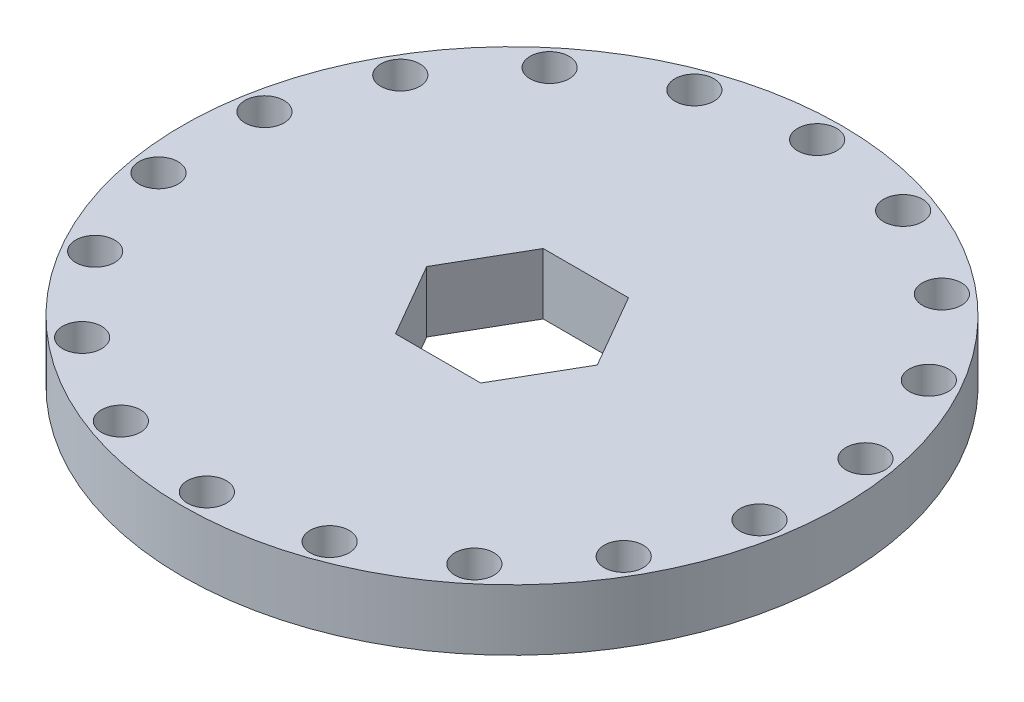
SolidWorks part; units mm, degrees
ref_plane "前视基准面" through (0, 0, 0) normal (0, 0, 1) x (1, 0, 0)
ref_plane "上视基准面" through (0, 0, 0) normal (0, 1, 0) x (1, 0, 0)
ref_plane "右视基准面" through (0, 0, 0) normal (1, 0, 0) x (0, 0, -1)
sketch "草图1" plane through (0, 0, 0) normal (0, 1, 0) x (1, 0, 0)
  circle A0 centre (0, 0) radius 27
  circle A1 centre (0, 0) radius 8
  circle A6 centre (0, 0) radius 2
extrude "凸台-拉伸1" add sketch "草图1" along normal blind 5
sketch "草图2" plane through (0, 5, 0) normal (0, 1, 0) x (1, 0, 0)
  line L1 (-3.493, -6.05) -> (3.493, -6.05)
  line L2 (3.493, -6.05) -> (6.9859, 0)
  line L3 (6.9859, 0) -> (3.493, 6.05)
  line L4 (3.493, 6.05) -> (-3.493, 6.05)
  line L5 (-3.493, 6.05) -> (-6.9859, 0)
  line L6 (-6.9859, 0) -> (-3.493, -6.05)
  circle A0 centre (0, 0) radius 6.05 construction
  dimension "D1" = 12.1
extrude "切除-拉伸1" cut sketch "草图2" against normal blind 5
sketch "草图3" plane through (0, 5, 0) normal (0, 1, 0) x (1, 0, 0)
  circle A2 centre (0, 25) radius 1.6
  circle A3 centre (8.5505, 23.4923) radius 1.6
  circle A4 centre (16.0697, 19.1511) radius 1.6
  circle A5 centre (21.6506, 12.5) radius 1.6
  circle A6 centre (24.6202, 4.3412) radius 1.6
  circle A7 centre (24.6202, -4.3412) radius 1.6
  circle A8 centre (21.6506, -12.5) radius 1.6
  circle A9 centre (16.0697, -19.1511) radius 1.6
  circle A10 centre (8.5505, -23.4923) radius 1.6
  circle A11 centre (0, -25) radius 1.6
  circle A12 centre (-8.5505, -23.4923) radius 1.6
  circle A13 centre (-16.0697, -19.1511) radius 1.6
  circle A14 centre (-21.6506, -12.5) radius 1.6
  circle A15 centre (-24.6202, -4.3412) radius 1.6
  circle A16 centre (-24.6202, 4.3412) radius 1.6
  circle A17 centre (-21.6506, 12.5) radius 1.6
  circle A18 centre (-16.0697, 19.1511) radius 1.6
  circle A19 centre (-8.5505, 23.4923) radius 1.6
extrude "切除-拉伸2" cut sketch "草图3" against normal blind 10
